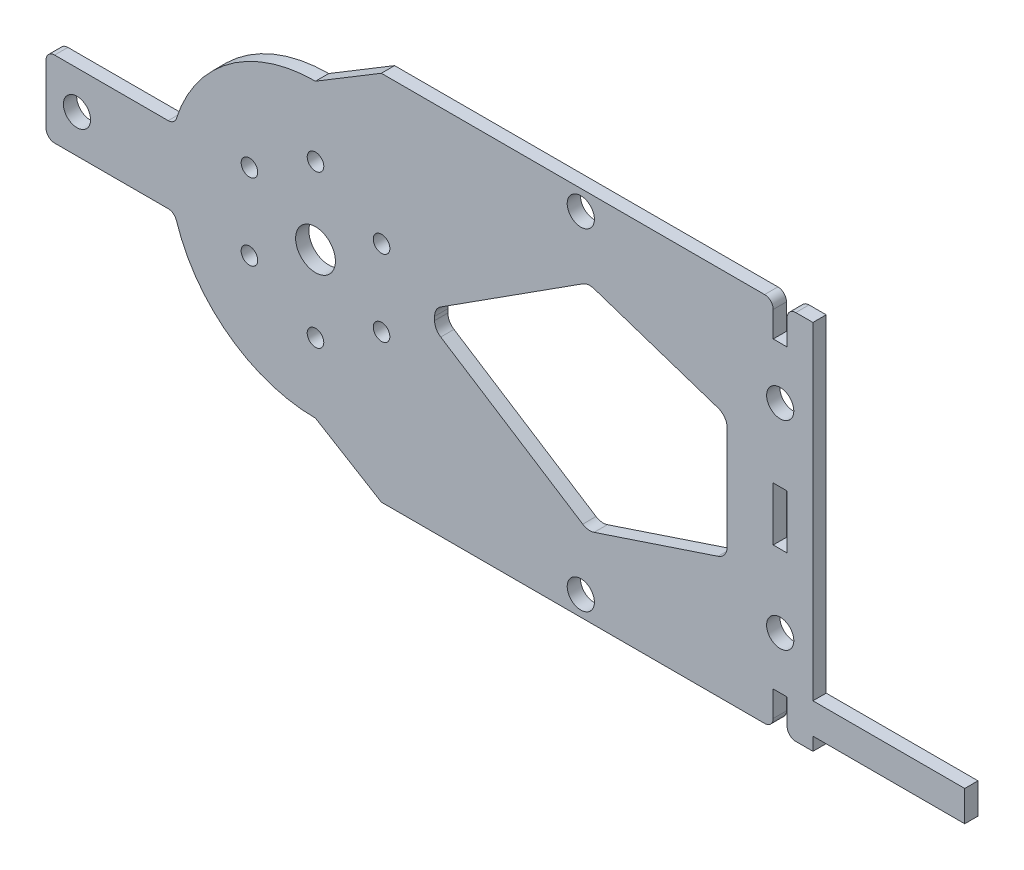
SolidWorks part; units mm, degrees
ref_plane "前视基准面" through (0, 0, 0) normal (0, 0, 1) x (1, 0, 0)
ref_plane "上视基准面" through (0, 0, 0) normal (0, 1, 0) x (1, 0, 0)
ref_plane "右视基准面" through (0, 0, 0) normal (1, 0, 0) x (0, 0, -1)
sketch "草图1" plane through (0, 0, 0) normal (0, 0, 1) x (1, 0, 0)
  line L0 (31.0657, 12.95) -> (31.0657, 17.05) construction
  line L1 (30.0157, 28) -> (32.1157, 28) construction
  line L2 (32.1157, -4.05) -> (30.0157, -4.05)
  line L3 (32.1157, -4.05) -> (32.1157, 4.05)
  line L4 (32.1157, 4.05) -> (30.0157, 4.05)
  line L5 (30.0157, -4.05) -> (30.0157, 4.05)
  line L6 (32.1157, -4.05) -> (30.0157, 4.05) construction
  line L7 (32.1157, 4.05) -> (30.0157, -4.05) construction
  line L8 (32.1157, 28) -> (32.1157, 22.85)
  line L9 (30.0157, 22.85) -> (32.1157, 22.85)
  line L10 (30.0157, 28) -> (30.0157, 22.85)
  line L11 (31.0657, 0) -> (29.7708, 0) construction
  line L12 (30.0157, -28) -> (32.1157, -28) construction
  line L13 (31.0657, -12.95) -> (31.0657, -17.05) construction
  line L14 (30.0157, -28) -> (30.0157, -22.85)
  line L15 (30.0157, -22.85) -> (32.1157, -22.85)
  line L16 (32.1157, -28) -> (32.1157, -22.85)
  line L17 (32.1157, -28) -> (36.001, -28)
  line L18 (36.001, -28) -> (36.001, 28) construction
  line L19 (36.001, 28) -> (32.1157, 28)
  line L23 (-38.999, -22.002) -> (-29.075, -28)
  line L25 (-38.999, 22.002) -> (-29.075, 28)
  line L29 (30.0157, -28) -> (-29.075, -28)
  line L30 (-29.075, 28) -> (30.0157, 28)
  line L31 (-29.075, -28) -> (-29.075, 28) construction
  line L34 (-48.9583, 5.75) -> (-48.9583, -5.75) construction
  line L41 (31.0657, -15) -> (31.0657, 15) construction
  line L42 (31.0657, 15) -> (1.001, 25) construction
  line L43 (1.001, 25) -> (-29.0397, 5.75) construction
  line L44 (-29.0397, 5.75) -> (-29.0397, -5.75) construction
  line L45 (-29.0397, -5.75) -> (1.001, -25) construction
  line L46 (1.001, -25) -> (31.0657, -15) construction
  line L47 (2.1009, -16.2032) -> (23.0657, -9.23)
  line L48 (23.0657, -9.23) -> (23.0657, 9.23)
  line L49 (23.0657, 9.23) -> (2.1009, 16.2032)
  line L50 (2.1009, 16.2032) -> (-21.0397, 1.3748)
  line L51 (-21.0397, 1.3748) -> (-21.0397, -1.3748)
  line L52 (-21.0397, -1.3748) -> (2.1009, -16.2032)
  line L53 (-74.9583, 0) -> (-38.999, 0) construction
  line L54 (-38.999, 0) -> (77.0107, 0) construction
  line L55 (-60.2364, -5.75) -> (-79.6313, -5.75)
  line L56 (-79.6313, -5.75) -> (-79.6313, 5.75)
  line L57 (-79.6313, 5.75) -> (-60.2364, 5.75)
  line L58 (36.001, -21.4019) -> (58.8883, -21.4019)
  line L59 (58.8883, -21.4019) -> (58.8883, -26.0177)
  line L60 (58.8883, -26.0177) -> (36.001, -26.0177)
  line L61 (36.001, -21.4019) -> (36.001, 28)
  line L62 (36.001, -26.0177) -> (36.001, -28)
  circle A0 centre (31.0657, 15) radius 2.05
  circle A1 centre (31.0657, -15) radius 2.05
  circle A3 centre (-38.999, 0) radius 3
  circle A6 centre (-38.999, 0) radius 11.5 construction
  circle A7 centre (-38.999, -11.5) radius 1.25
  circle A18 centre (-38.999, 0) radius 22.002 construction
  circle A25 centre (-48.9583, -5.75) radius 1.25
  circle A26 centre (-48.9583, 5.75) radius 1.25
  circle A27 centre (-38.999, 11.5) radius 1.25
  circle A28 centre (-29.0397, 5.75) radius 1.25
  circle A29 centre (-29.0397, -5.75) radius 1.25
  circle A30 centre (1.001, -25) radius 2.05
  circle A31 centre (1.001, 25) radius 2.05
  arc A32 (-38.999, -22.002) -> (-60.2364, -5.75) centre (-38.999, 0) cw
  arc A33 (-60.2364, 5.75) -> (-38.999, 22.002) centre (-38.999, 0) cw
  circle A34 centre (-74.9583, 0) radius 2.05
  point P4 (31.0657, 0)
  dimension "D3" = 6
  dimension "D4" = 75
  dimension "D5" = 6
  dimension "D6" = 11.5
  dimension "D7" = 23
  dimension "D8" = 2.5
  dimension "D9" = 40
  dimension "D11" = 3
  dimension "D19" = 28
  dimension "D1" = 8.1
  dimension "D2" = 2.1
  dimension "D10" = 3
  dimension "D12" = 40
  dimension "D13" = 26
  dimension "D15" = 3.8853
  dimension "D16" = 2.1
  dimension "D18" = 30
  dimension "D17" = 8
extrude "凸台-拉伸1" add sketch "草图1" along normal blind 2
fillet "圆角1" radius 1.3 8 edges at (-79.6313, 5.75, 1) (-79.6313, -5.75, 1) (-60.2364, -5.75, 1) (-60.2364, 5.75, 1) (32.1157, -28, 1) (30.0157, -28, 1) (32.1157, 28, 1) (30.0157, 28, 1)
fillet "圆角2" radius 2 6 edges at (23.0657, 9.23, 1) (23.0657, -9.23, 1) (2.1009, -16.2032, 1) (2.1009, 16.2032, 1) (-21.0397, 1.3748, 1) (-21.0397, -1.3748, 1)
